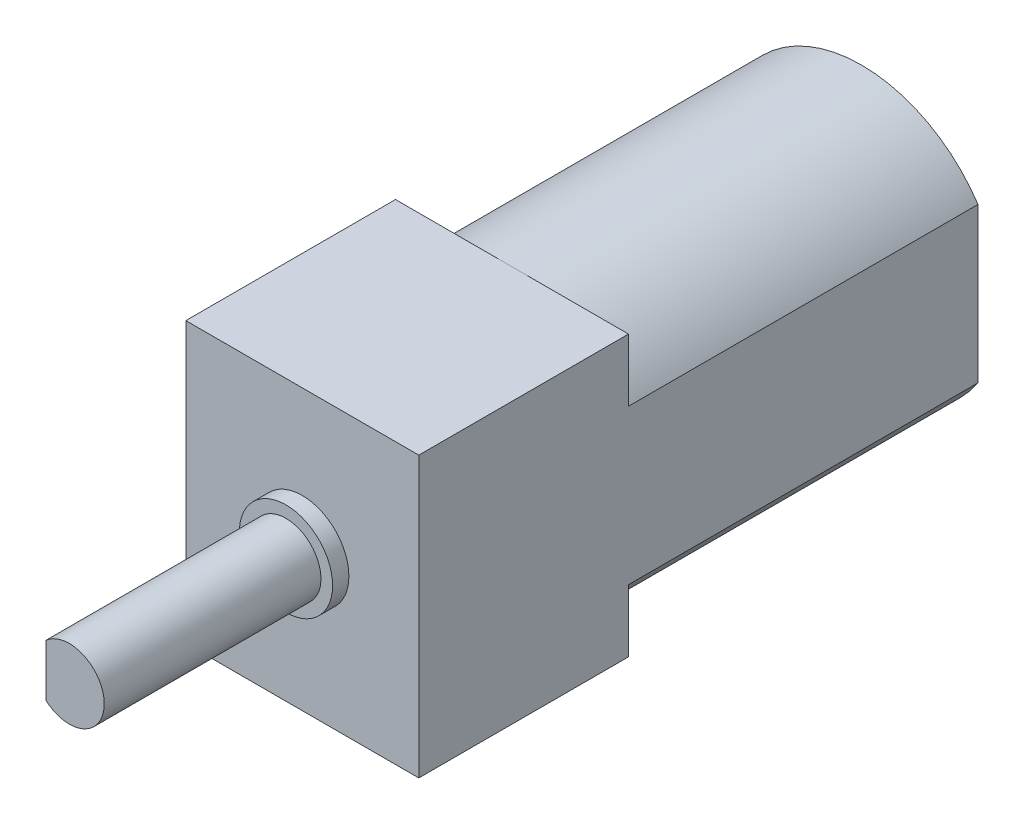
SolidWorks part; units mm, degrees
ref_plane "前视基准面" through (0, 0, 0) normal (0, 0, 1) x (1, 0, 0)
ref_plane "上视基准面" through (0, 0, 0) normal (0, 1, 0) x (1, 0, 0)
ref_plane "右视基准面" through (0, 0, 0) normal (1, 0, 0) x (0, 0, -1)
sketch "草图1" plane through (0, 0, 0) normal (0, 0, 1) x (1, 0, 0)
  line L1 (5, 0) -> (5, 6)
  line L2 (5, 6) -> (-5, 6)
  line L3 (-5, 6) -> (-5, -6)
  line L4 (-5, -6) -> (5, -6)
  line L5 (5, -6) -> (5, 0)
extrude "凸台-拉伸1" add sketch "草图1" along normal blind 24
sketch "草图2" plane through (0, 0, 0) normal (0, 0, -1) x (-1, 0, 0)
  circle A0 centre (0, 0) radius 2.5
extrude "凸台-拉伸2" add sketch "草图2" along normal blind 1.2
sketch "草图3" plane through (0, 0, 24) normal (0, 0, 1) x (1, 0, 0)
  circle A0 centre (0, 0) radius 2
extrude "凸台-拉伸3" add sketch "草图3" along normal blind 0.7
sketch "草图5" plane through (0, 0, 24.7) normal (0, 0, 1) x (1, 0, 0)
  circle A0 centre (0, 0) radius 1.5
extrude "凸台-拉伸5" add sketch "草图5" along normal blind 9.3
sketch "草图6" plane through (0, 0, 0) normal (0, 0, -1) x (-1, 0, 0)
  circle A0 centre (0, 0) radius 6
  circle A1 centre (0, 0) radius 8.808
extrude "切除-拉伸1" cut sketch "草图6" against normal blind 15 contours A0 | A1
sketch "草图7" plane through (0, 0, 34) normal (0, 0, 1) x (1, 0, 0)
  line L1 (-1, 0) -> (-1, 3.3423)
  line L2 (-1, 3.3423) -> (-2.5734, 3.3423)
  line L3 (-2.5734, 3.3423) -> (-2.5734, -2.2112)
  line L4 (-2.5734, -2.2112) -> (-1, -2.2112)
  line L5 (-1, -2.2112) -> (-1, 0)
extrude "切除-拉伸2" cut sketch "草图7" against normal blind 9.3
